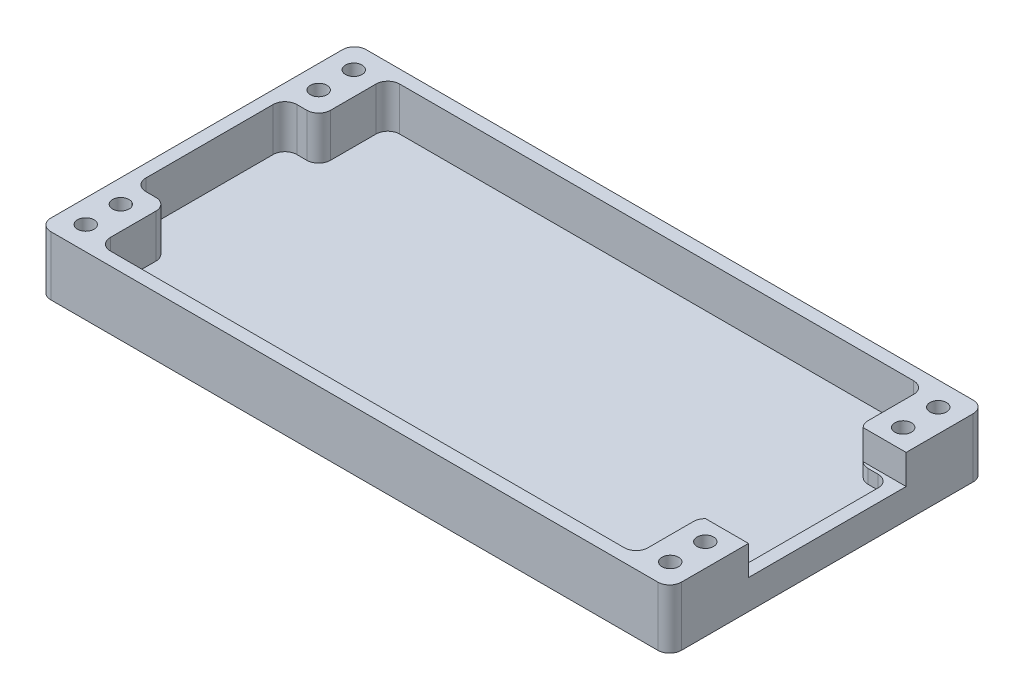
SolidWorks part; units mm, degrees
ref_plane "Спереди" through (0, 0, 0) normal (0, 0, 1) x (1, 0, 0)
ref_plane "Сверху" through (0, 0, 0) normal (0, 1, 0) x (1, 0, 0)
ref_plane "Справа" through (0, 0, 0) normal (1, 0, 0) x (0, 0, -1)
sketch "Эскиз1" plane through (0, 0, 0) normal (0, 1, 0) x (1, 0, 0)
  line L1 (-77, -40) -> (77, -40)
  line L2 (-80, -37) -> (-80, 37)
  line L3 (-77, 40) -> (77, 40)
  line L4 (80, -37) -> (80, 37)
  line L5 (-80, -40) -> (80, 40) construction
  line L6 (-80, 40) -> (80, -40) construction
  arc A0 (-77, -40) -> (-80, -37) centre (-77, -37) cw
  arc A1 (-80, 37) -> (-77, 40) centre (-77, 37) cw
  arc A2 (77, 40) -> (80, 37) centre (77, 37) cw
  arc A3 (77, -40) -> (80, -37) centre (77, -37) ccw
  point P0 (0, 0)
  dimension "D3" = 3
  dimension "D1" = 160
  dimension "D2" = 80
extrude "Бобышка-Вытянуть1" add sketch "Эскиз1" along normal blind 15
sketch "Эскиз2" plane through (0, 15, 0) normal (0, 1, 0) x (1, 0, 0)
  line L1 (-75.75, -36.7) -> (75.75, -36.7)
  line L2 (-76.75, -35.7) -> (-76.75, 35.7)
  line L3 (-75.75, 36.7) -> (75.75, 36.7)
  line L4 (76.75, -35.7) -> (76.75, 35.7)
  line L5 (-76.75, -36.7) -> (76.75, 36.7) construction
  line L6 (-76.75, 36.7) -> (76.75, -36.7) construction
  arc A0 (-75.75, -36.7) -> (-76.75, -35.7) centre (-75.75, -35.7) cw
  arc A1 (75.75, -36.7) -> (76.75, -35.7) centre (75.75, -35.7) ccw
  arc A2 (75.75, 36.7) -> (76.75, 35.7) centre (75.75, 35.7) cw
  arc A3 (-76.75, 35.7) -> (-75.75, 36.7) centre (-75.75, 35.7) cw
  point P0 (0, 0)
  dimension "D3" = 1
  dimension "D1" = 153.5
  dimension "D2" = 73.4
extrude "Вырез-Вытянуть1" cut sketch "Эскиз2" against normal offset from surface (11 mm away) 4 up to face at (0, 0, 0)
sketch "Эскиз3" plane through (0, 4, 0) normal (0, 1, 0) x (1, 0, 0)
  line L0 (-76.75, 35.7) -> (-76.75, -35.7) construction
  line L1 (-76.75, -36.7) -> (-68.2, -36.7)
  line L2 (-76.75, -36.7) -> (-76.75, -19.15)
  line L3 (-76.75, -19.15) -> (-71.2, -19.15)
  line L4 (-68.2, -36.7) -> (-68.2, -22.15)
  line L5 (-75.75, -36.7) -> (75.75, -36.7) construction
  line L6 (0, 0) -> (-76.75, 0) construction
  line L7 (-76.75, 35.7) -> (-76.75, -35.7) construction
  line L8 (0, 0) -> (0, -36.7) construction
  line L9 (-68.2, 36.7) -> (-68.2, 22.15)
  line L10 (-76.75, 19.15) -> (-71.2, 19.15)
  line L11 (-76.75, 36.7) -> (-76.75, 19.15)
  line L12 (-76.75, 36.7) -> (-68.2, 36.7)
  line L13 (76.75, 36.7) -> (68.2, 36.7)
  line L14 (76.75, 36.7) -> (76.75, 19.15)
  line L15 (76.75, 19.15) -> (71.2, 19.15)
  line L16 (68.2, 36.7) -> (68.2, 22.15)
  line L17 (68.2, -36.7) -> (68.2, -22.15)
  line L18 (76.75, -19.15) -> (71.2, -19.15)
  line L19 (76.75, -36.7) -> (76.75, -19.15)
  line L20 (76.75, -36.7) -> (68.2, -36.7)
  arc A0 (68.2, -22.15) -> (71.2, -19.15) centre (71.2, -22.15) cw
  arc A1 (71.2, 19.15) -> (68.2, 22.15) centre (71.2, 22.15) cw
  arc A2 (-68.2, 22.15) -> (-71.2, 19.15) centre (-71.2, 22.15) cw
  arc A3 (-71.2, -19.15) -> (-68.2, -22.15) centre (-71.2, -22.15) cw
  point P29 (68.2, -19.15)
  point P32 (68.2, 19.15)
  point P35 (-68.2, 19.15)
  point P38 (-68.2, -19.15)
  dimension "D3" = 3
  dimension "D1" = 38.3
  dimension "D2" = 136.4
extrude "Бобышка-Вытянуть2" add sketch "Эскиз3" along normal up to surface (11 mm away) up to face at (0, 15, 0)
sketch "Эскиз4" plane through (0, 15, 0) normal (0, 1, 0) x (1, 0, 0)
  line L0 (0, 0) -> (-76.75, 0) construction
  line L1 (-76.75, 19.15) -> (-76.75, -19.15) construction
  line L2 (0, 0) -> (0, -36.7) construction
  line L3 (-68.2, -36.7) -> (68.2, -36.7) construction
  circle A0 centre (-74.15, -34) radius 2.1
  circle A2 centre (-74.15, 34) radius 2.1
  circle A3 centre (74.15, 34) radius 2.1
  circle A4 centre (74.15, -34) radius 2.1
  circle A5 centre (-74.15, -25.1) radius 2.1
  circle A6 centre (-74.15, 25.1) radius 2.1
  circle A7 centre (74.15, 25.1) radius 2.1
  circle A8 centre (74.15, -25.1) radius 2.1
  dimension "D3" = 4.2
  dimension "D1" = 68
  dimension "D2" = 148.3
  dimension "D4" = 50.2
extrude "Вырез-Вытянуть2" cut sketch "Эскиз4" against normal through all
fillet "Скругление1" radius 3 8 edges at (68.2, 9.5, 36.7) (76.75, 9.5, 19.15) (68.2, 9.5, -36.7) (76.75, 9.5, -19.15) (-68.2, 9.5, 36.7) (-76.75, 9.5, 19.15) (-76.75, 9.5, -19.15) (-68.2, 9.5, -36.7)
sketch "Эскиз5" plane through (80, 0, 0) normal (1, 0, 0) x (0, 0, -1)
  line L0 (-37, 0) -> (37, 0) construction
  line L1 (20, 47.5) -> (-20, 47.5)
  line L2 (20, 47.5) -> (20, 7.5)
  line L3 (20, 7.5) -> (-20, 7.5)
  line L4 (-20, 47.5) -> (-20, 7.5)
  line L5 (20, 47.5) -> (-20, 7.5) construction
  line L6 (20, 7.5) -> (-20, 47.5) construction
  point P0 (0, 27.5)
  point P7 (0, 0)
  dimension "D1" = 40
  dimension "D2" = 7.5
extrude "Вырез-Вытянуть3" cut sketch "Эскиз5" against normal up to surface (11.8 mm away) up to face at (68.2, 9.5, -27.925)
